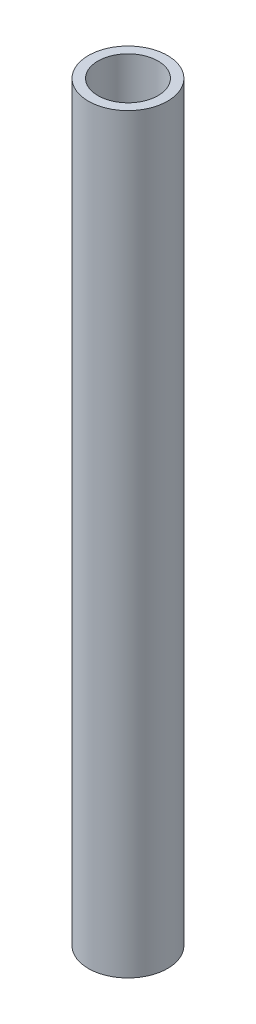
SolidWorks part; units mm, degrees
ref_plane "Front Plane" through (0, 0, 0) normal (0, 0, 1) x (1, 0, 0)
ref_plane "Top Plane" through (0, 0, 0) normal (0, 1, 0) x (1, 0, 0)
ref_plane "Right Plane" through (0, 0, 0) normal (1, 0, 0) x (0, 0, -1)
sketch "Sketch1" plane through (0, 0, 0) normal (0, 1, 0) x (1, 0, 0)
  circle A0 centre (0, 0) radius 1.054
  circle A1 centre (0, 0) radius 0.8
extrude "Boss-Extrude1" add sketch "Sketch1" along normal blind 20
